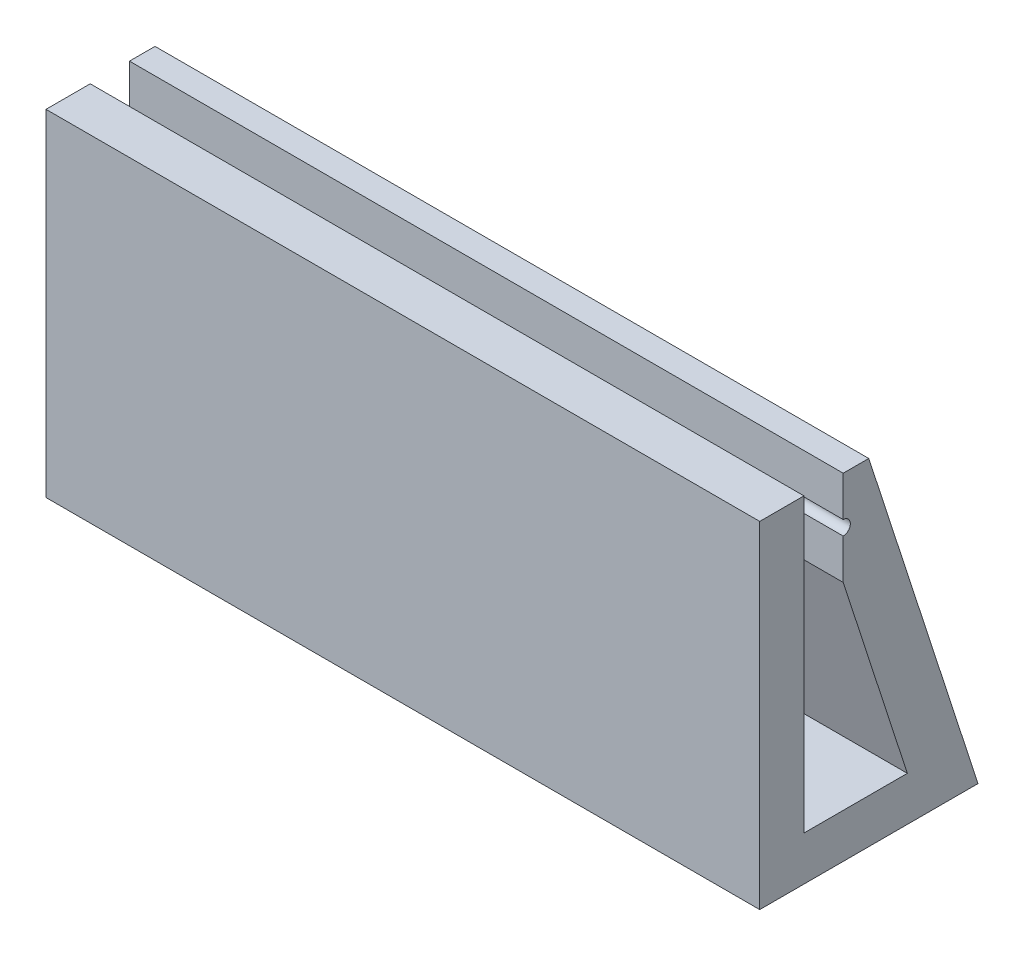
SolidWorks part; units mm, degrees
ref_plane "Front Plane" through (0, 0, 0) normal (0, 0, 1) x (1, 0, 0)
ref_plane "Top Plane" through (0, 0, 0) normal (0, 1, 0) x (1, 0, 0)
ref_plane "Right Plane" through (0, 0, 0) normal (1, 0, 0) x (0, 0, -1)
sketch "Sketch1" plane through (0, 0, 0) normal (1, 0, 0) x (0, 0, -1)
  line L0 (0, 0) -> (6.1164, 0)
  line L1 (0, 5.3304) -> (1.2392, 5.3304) construction
  line L2 (2.3392, 9.4216) -> (2.3392, 6.771) construction
  line L3 (2.3392, 6.771) -> (4.1366, 1.2392)
  line L4 (4.1366, 1.2392) -> (1.2392, 1.2392)
  line L5 (1.2392, 1.2392) -> (1.2392, 9.4216)
  line L6 (1.2392, 9.4216) -> (0, 9.4216)
  line L7 (0, 9.4216) -> (0, 0)
  line L8 (2.3392, 9.4216) -> (2.3392, 8.2963)
  line L9 (2.3392, 7.8963) -> (2.3392, 6.771)
  line L10 (2.3392, 9.4216) -> (3.0551, 9.4216)
  line L11 (3.0551, 9.4216) -> (6.1164, 0)
  line L12 (2.6879, 1.2392) -> (2.6879, 0) construction
  arc A0 (2.3392, 8.2963) -> (2.3392, 7.8963) centre (2.3392, 8.0963) cw
  dimension "D1" = 0.2
  dimension "D2" = 1.1
  dimension "D3" = 72
  dimension "D4" = 1.5
extrude "Boss-Extrude1" add sketch "Sketch1" along normal mid plane 20 contours L8 A0 L9 L3 L4 L5 L6 L7 L0 L11 L10
